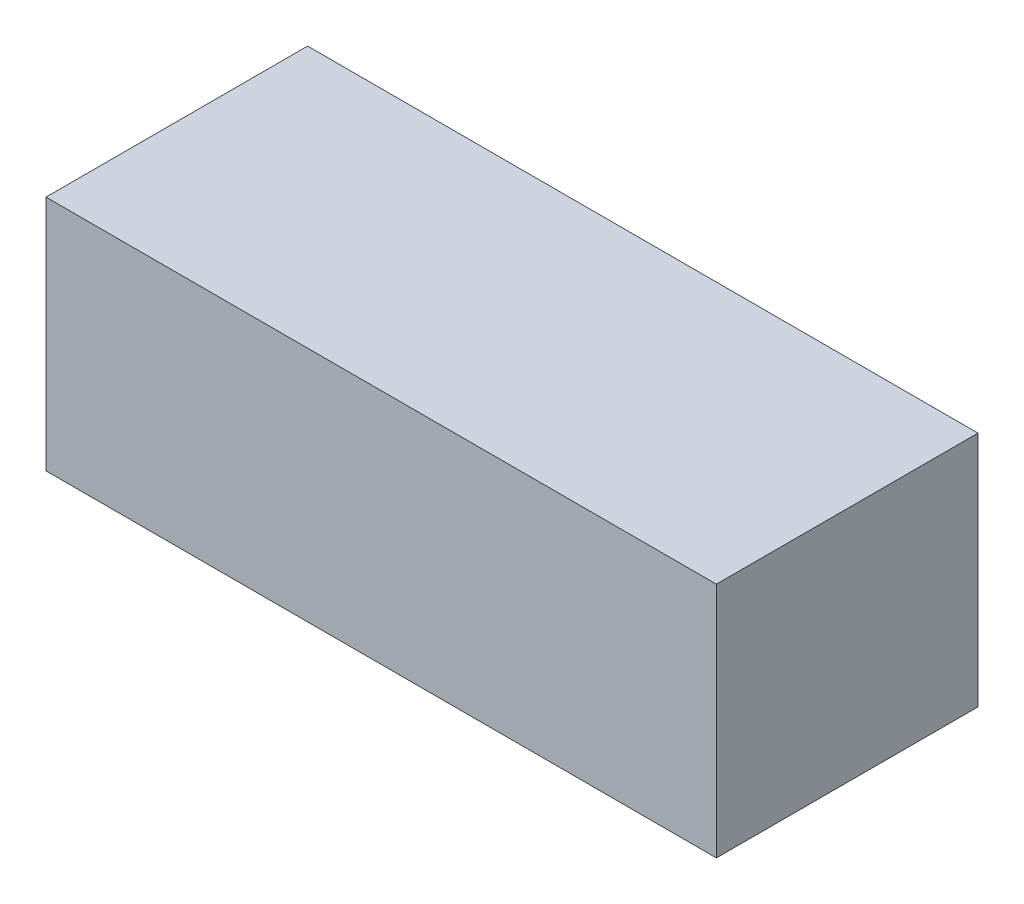
SolidWorks part; units mm, degrees
ref_plane "Front Plane" through (0, 0, 0) normal (0, 0, 1) x (1, 0, 0)
ref_plane "Top Plane" through (0, 0, 0) normal (0, 1, 0) x (1, 0, 0)
ref_plane "Right Plane" through (0, 0, 0) normal (1, 0, 0) x (0, 0, -1)
sketch "Sketch1" plane through (0, 0, 0) normal (0, 0, 1) x (1, 0, 0)
  line L0 (-250, 12.5) -> (-250, -12.5) construction
  line L1 (155, 72.5) -> (-255, 72.5)
  line L2 (155, 72.5) -> (155, -72.5)
  line L3 (155, -72.5) -> (-255, -72.5)
  line L4 (-255, 72.5) -> (-255, -72.5)
  line L5 (-150, 62.5) -> (150, 62.5) construction
  line L6 (150, -62.5) -> (150, 62.5) construction
  line L7 (-150, -62.5) -> (150, -62.5) construction
  line L8 (-250, 62.5) -> (-250, -62.5) construction
  line L9 (-250, 62.5) -> (150, 62.5) construction
  line L10 (150, -62.5) -> (150, 62.5) construction
  line L11 (-250, -62.5) -> (150, -62.5) construction
  point P6 (-250, -62.5)
  point P9 (-247.381, 62.5)
  point P12 (-250, 62.5)
  point P14 (-252.3368, 62.5)
  point P16 (-246.3191, -62.5)
  dimension "D1" = 10
  dimension "D2" = 5
  dimension "D3" = 5
  dimension "D4" = 10
extrude "Boss-Extrude1" add sketch "Sketch1" against normal offset from surface 5 and the other way offset from surface (80 mm away) 5
